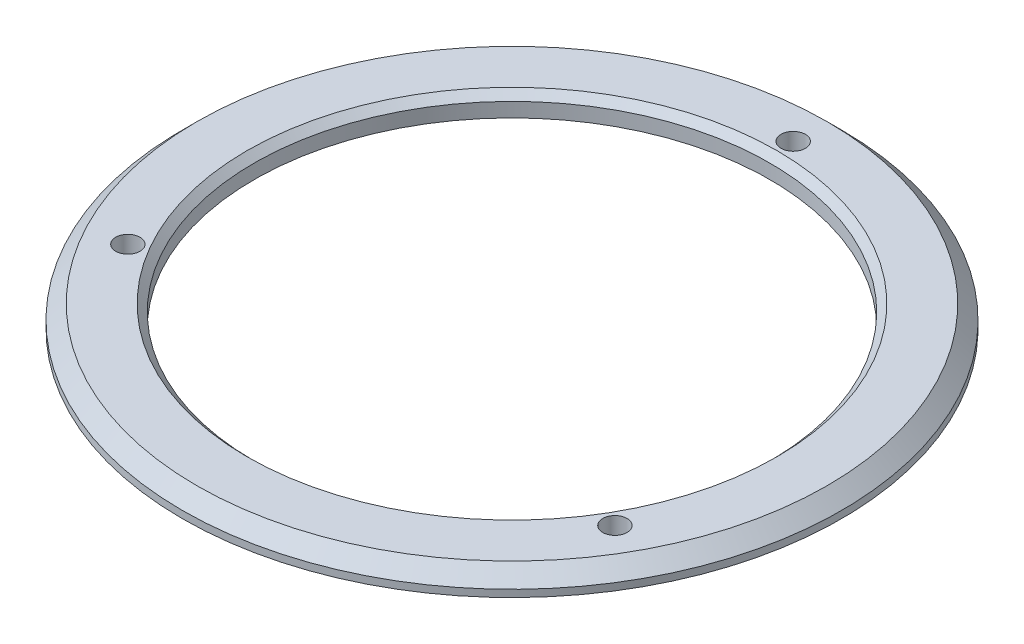
SolidWorks part; units mm, degrees
material "PLA"
ref_plane "Front Plane" through (0, 0, 0) normal (0, 0, 1) x (1, 0, 0)
ref_plane "Top Plane" through (0, 0, 0) normal (0, 1, 0) x (1, 0, 0)
ref_plane "Right Plane" through (0, 0, 0) normal (1, 0, 0) x (0, 0, -1)
sketch "Sketch1" plane through (0, 0, 0) normal (0, 1, 0) x (1, 0, 0)
  circle A0 centre (0, 0) radius 46
  circle A1 centre (0, 0) radius 36
  dimension "D1" = 72
  dimension "D2" = 92
extrude "Boss-Extrude1" add sketch "Sketch1" along normal blind 3
chamfer "Chamfer1" distance 2 angle 45 1 edges at (0, 3, 46)
sketch "Sketch2" plane through (0, 3, 0) normal (0, 1, 0) x (1, 0, 0)
  line L0 (0, -1000) -> (0, 49000) construction
  circle A0 centre (0, 0) radius 46 construction
  circle A1 centre (0, 39.251) radius 1.7
  point P1 (0, 46)
  dimension "D1" = 3.4
  dimension "D2" = 6.749
extrude "Cut-Extrude1" cut sketch "Sketch2" against normal through all
pattern_circular "CirPattern1" count 3 over 360 about axis through (0, 0, 0) along (0, 1, 0) of "Cut-Extrude1"
chamfer "Chamfer2" distance 1 angle 45 1 edges at (0, 3, 36)
